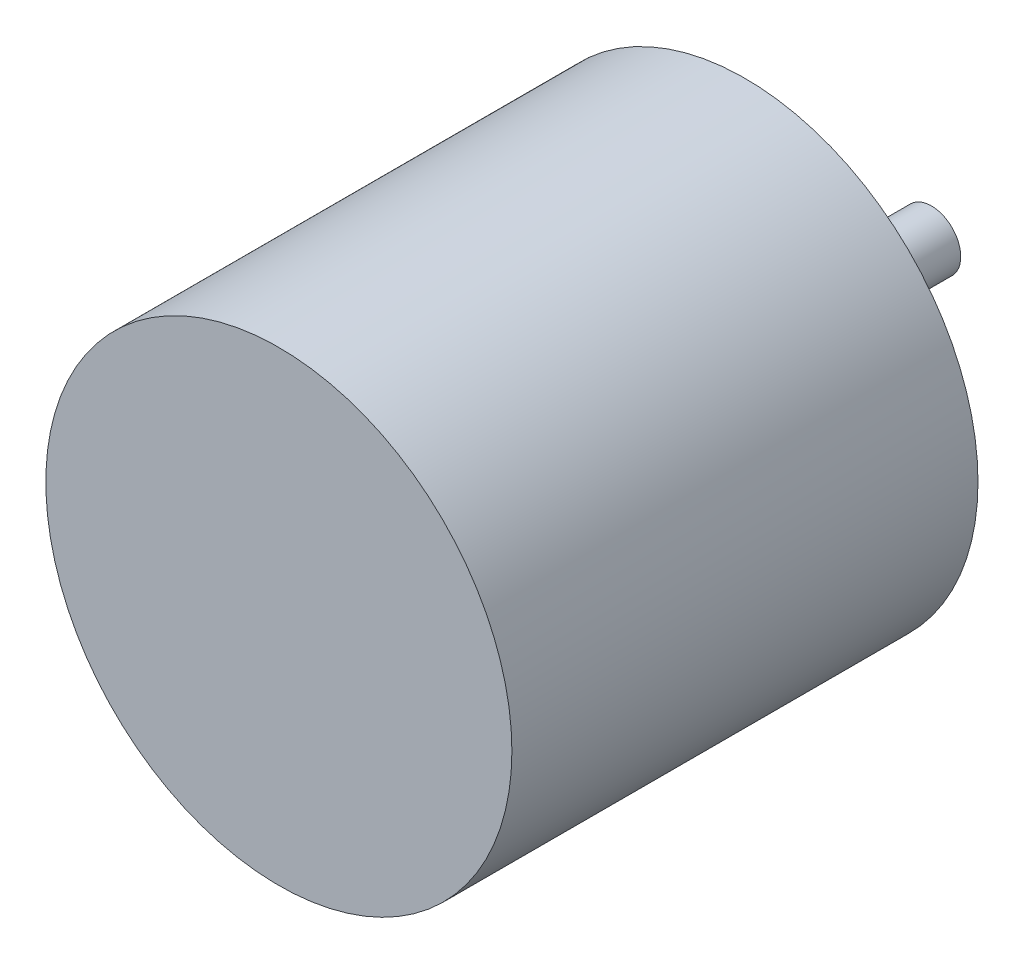
SolidWorks part; units mm, degrees
ref_plane "Front Plane" through (0, 0, 0) normal (0, 0, 1) x (1, 0, 0)
ref_plane "Top Plane" through (0, 0, 0) normal (0, 1, 0) x (1, 0, 0)
ref_plane "Right Plane" through (0, 0, 0) normal (1, 0, 0) x (0, 0, -1)
sketch "Sketch1" plane through (0, 0, 0) normal (0, 0, 1) x (1, 0, 0)
  circle A0 centre (0, 0) radius 12.5
  dimension "D1" = 25
extrude "Boss-Extrude1" add sketch "Sketch1" along normal blind 25
sketch "Sketch2" plane through (0, 0, 0) normal (0, 0, 1) x (1, 0, 0)
  circle A0 centre (0, 0) radius 1.5743
extrude "Boss-Extrude2" add sketch "Sketch2" against normal blind 10
